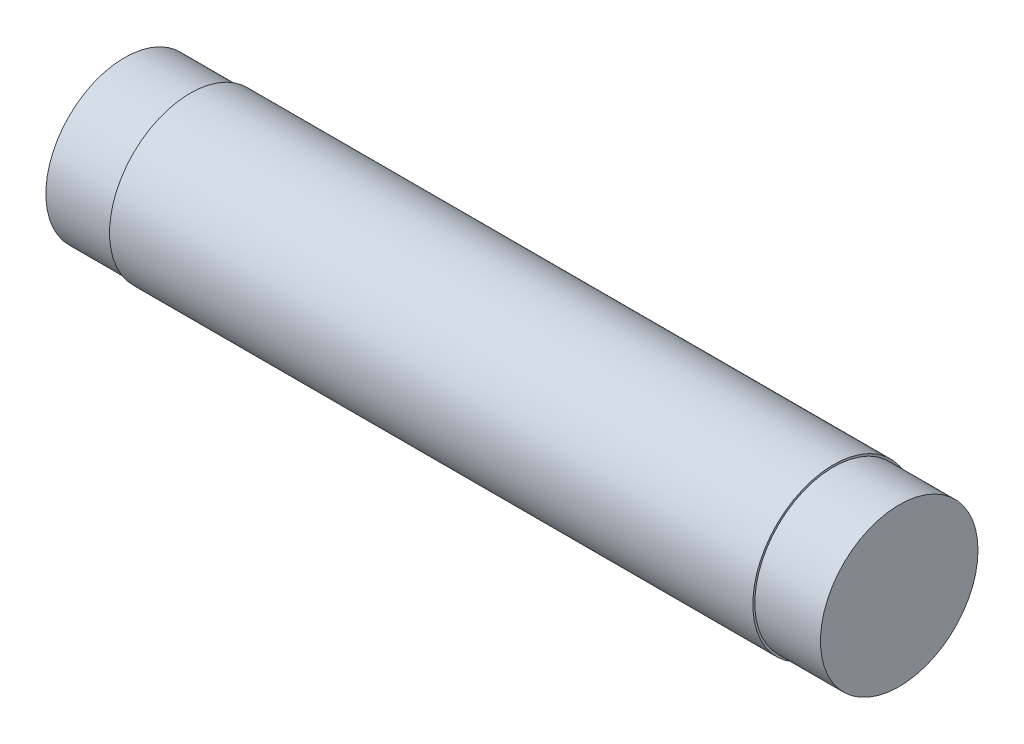
SolidWorks part; units mm, degrees
ref_plane "Front Plane" through (0, 0, 0) normal (0, 0, 1) x (1, 0, 0)
ref_plane "Top Plane" through (0, 0, 0) normal (0, 1, 0) x (1, 0, 0)
ref_plane "Right Plane" through (0, 0, 0) normal (1, 0, 0) x (0, 0, -1)
sketch "Sketch1" plane through (0, 0, 0) normal (1, 0, 0) x (0, 0, -1)
  circle A0 centre (0, 0) radius 6.15
  dimension "D1" = 12.3
extrude "Boss-Extrude1" add sketch "Sketch1" along normal blind 59
sketch "Sketch2" plane through (59, 0, 0) normal (1, 0, 0) x (0, 0, -1)
  circle A0 centre (0, 0) radius 6
  circle M2 centre (0, 0) radius 6.15
  dimension "D1" = 12
extrude "Cut-Extrude1" cut sketch "Sketch2" against normal blind 5 contours A0 M2
ref_plane "Plane1" through (29.5, 0, 0) normal (1, 0, 0) x (0, 0, -1)
mirror "Mirror1" about plane through (29.5, 0, 0) normal (1, 0, 0) of "Cut-Extrude1"
